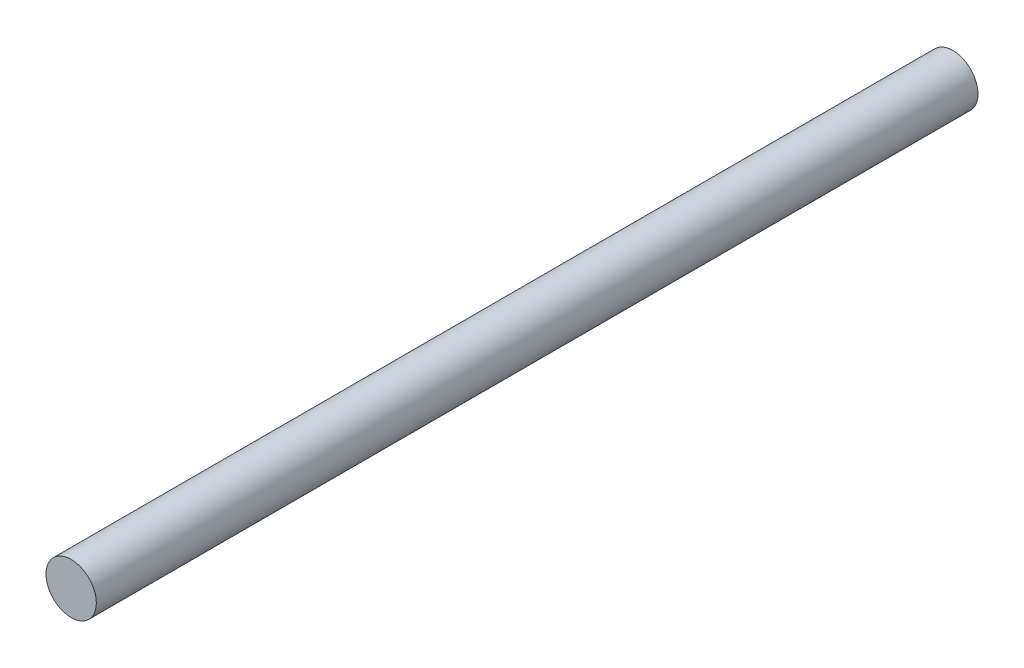
SolidWorks part; units mm, degrees
ref_plane "Front Plane" through (0, 0, 0) normal (0, 0, 1) x (1, 0, 0)
ref_plane "Top Plane" through (0, 0, 0) normal (0, 1, 0) x (1, 0, 0)
ref_plane "Right Plane" through (0, 0, 0) normal (1, 0, 0) x (0, 0, -1)
sketch "Sketch1" plane through (0, 0, 0) normal (0, 0, 1) x (1, 0, 0)
  circle A0 centre (0, 0) radius 2
extrude "Boss-Extrude1" add sketch "Sketch1" along normal blind 70
sketch "Sketch2" plane through (0, 0, 0) normal (0, 0, -1) x (-1, 0, 0)
  circle A0 centre (0, 0) radius 1
extrude "Cut-Extrude1" cut sketch "Sketch2" against normal blind 8
